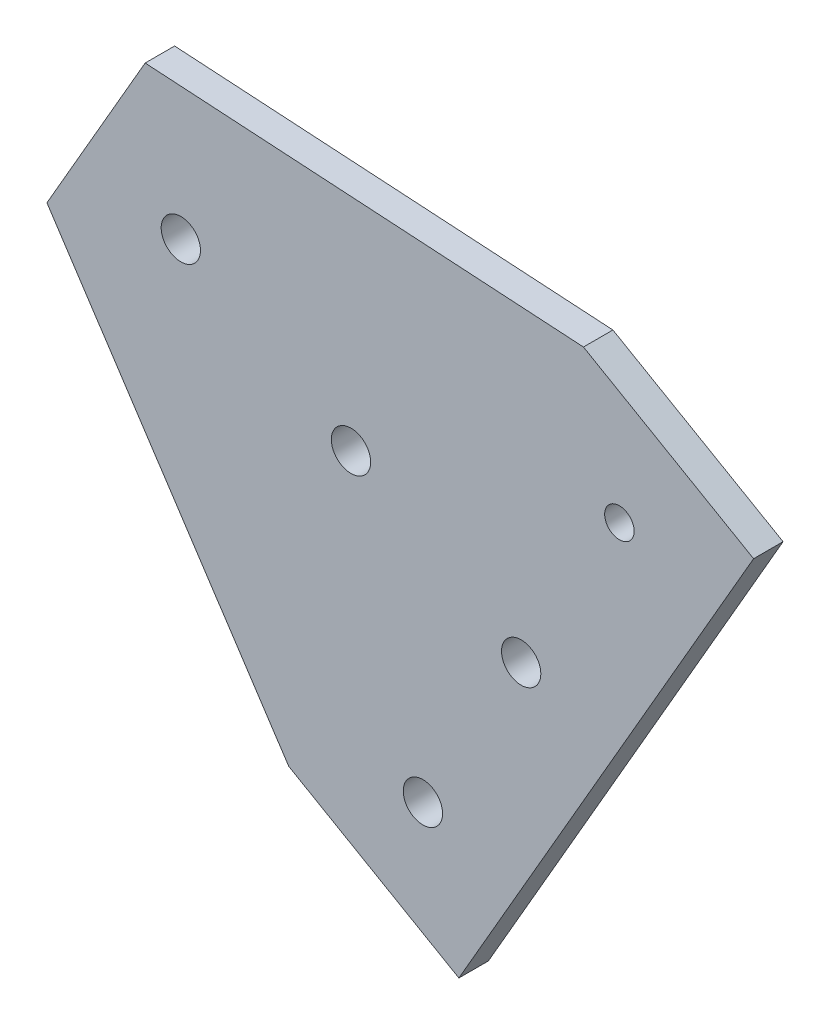
SolidWorks part; units mm, degrees
ref_plane "前视基准面" through (0, 0, 0) normal (0, 0, 1) x (1, 0, 0)
ref_plane "上视基准面" through (0, 0, 0) normal (0, 1, 0) x (1, 0, 0)
ref_plane "右视基准面" through (0, 0, 0) normal (1, 0, 0) x (0, 0, -1)
sketch "草图1" plane through (0, 0, 0) normal (0, 0, 1) x (1, 0, 0)
  line L0 (58.8532, -49.3184) -> (88.8532, 2.6432)
  line L1 (88.8532, 2.6432) -> (71.5327, 12.6432)
  line L2 (71.5327, 12.6432) -> (26.9208, 15.3714)
  line L3 (26.9208, 15.3714) -> (16.9208, -1.9491)
  line L4 (16.9208, -1.9491) -> (41.5334, -39.3188)
  line L5 (41.5334, -39.3188) -> (58.8532, -49.3184)
  circle A0 centre (55.1929, -35.6581) radius 2
  circle A1 centre (65.1929, -18.3376) radius 2
  circle A2 centre (75.1929, -1.0171) radius 1.5
  circle A3 centre (47.8724, -8.3376) radius 2
  circle A4 centre (30.5519, 1.6624) radius 2
extrude "凸台-拉伸1" add sketch "草图1" along normal blind 3
